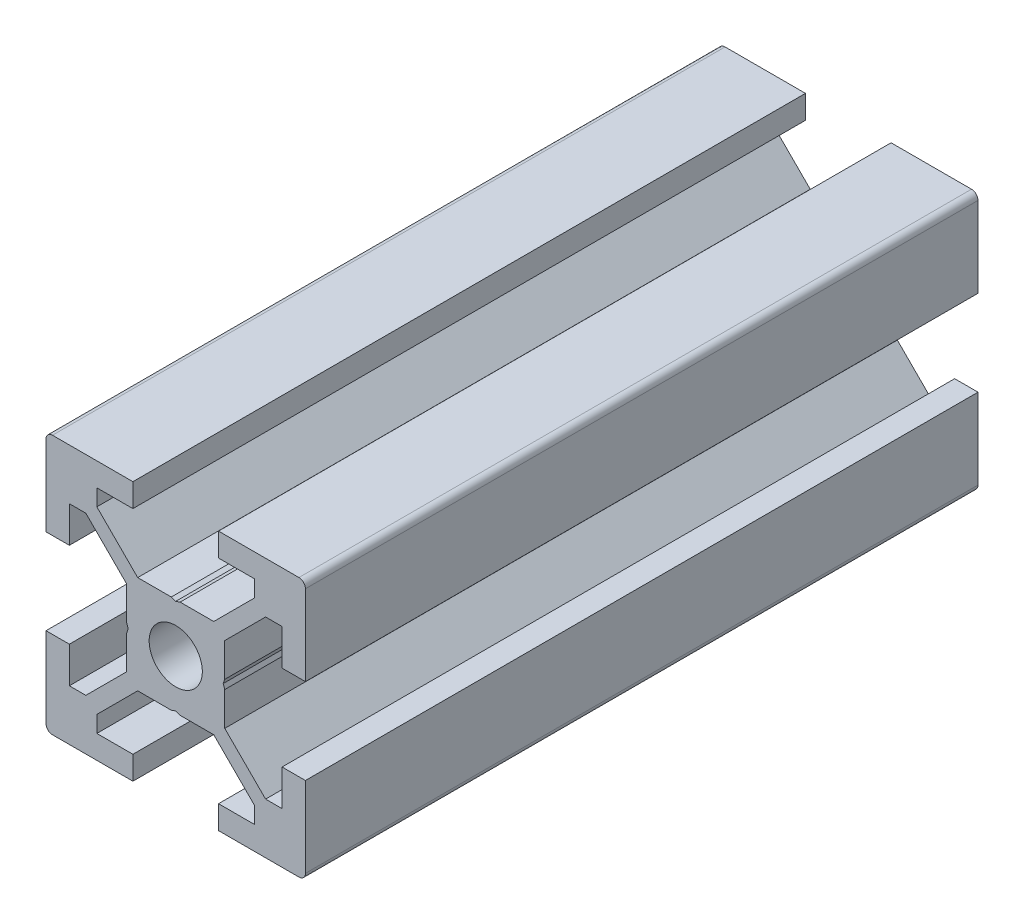
SolidWorks part; units mm, degrees
ref_plane "Front Plane" through (0, 0, 0) normal (0, 0, 1) x (1, 0, 0)
ref_plane "Top Plane" through (0, 0, 0) normal (0, 1, 0) x (1, 0, 0)
ref_plane "Right Plane" through (0, 0, 0) normal (1, 0, 0) x (0, 0, -1)
sketch "Sketch1" plane through (0, 0, 0) normal (0, 0, 1) x (1, 0, 0)
  line L0 (-3.3, 10) -> (-3.3, 8.2)
  line L1 (0, 0) -> (50000, 0) construction
  line L2 (-10, 3.3) -> (-10, 10)
  line L3 (-10, 10) -> (-3.3, 10)
  line L4 (0, 0) -> (0, 50000) construction
  line L5 (-10, -10) -> (10, 10) construction
  line L6 (-10, 10) -> (10, -10) construction
  line L7 (-2.9315, -3.78) -> (-0.34, -3.78)
  line L8 (-3.78, -2.9315) -> (-3.78, -0.34)
  line L9 (-2.9315, 3.78) -> (-0.34, 3.78)
  line L10 (3.78, -2.9315) -> (3.78, -0.34)
  line L11 (-3.78, -3.78) -> (3.78, 3.78) construction
  line L12 (-3.78, 3.78) -> (3.78, -3.78) construction
  line L13 (-6.08, 8.2) -> (-3.3, 8.2)
  line L14 (-8.2, 6.08) -> (-8.2, 3.3)
  line L15 (-8.2, 3.3) -> (-10, 3.3)
  line L16 (-8.2, 6.08) -> (-6.9285, 6.08)
  line L17 (-6.08, 8.2) -> (-6.08, 6.9285)
  line L18 (-6.9285, 6.08) -> (-3.78, 2.9315)
  line L19 (-6.08, 6.9285) -> (-2.9315, 3.78)
  line L20 (8.2, 6.08) -> (6.9285, 6.08)
  line L21 (8.2, 6.08) -> (8.2, 3.3)
  line L22 (8.2, 3.3) -> (10, 3.3)
  line L23 (10, 3.3) -> (10, 10)
  line L24 (10, 10) -> (3.3, 10)
  line L25 (3.3, 10) -> (3.3, 8.2)
  line L26 (6.08, 8.2) -> (3.3, 8.2)
  line L27 (6.08, 8.2) -> (6.08, 6.9285)
  line L28 (6.08, 6.9285) -> (2.9315, 3.78)
  line L29 (6.9285, 6.08) -> (3.78, 2.9315)
  line L30 (6.9285, -6.08) -> (3.78, -2.9315)
  line L31 (6.08, -6.9285) -> (2.9315, -3.78)
  line L32 (6.08, -8.2) -> (6.08, -6.9285)
  line L33 (6.08, -8.2) -> (3.3, -8.2)
  line L34 (3.3, -10) -> (3.3, -8.2)
  line L35 (10, -10) -> (3.3, -10)
  line L36 (10, -3.3) -> (10, -10)
  line L37 (8.2, -3.3) -> (10, -3.3)
  line L38 (8.2, -6.08) -> (8.2, -3.3)
  line L39 (8.2, -6.08) -> (6.9285, -6.08)
  line L40 (-6.08, -6.9285) -> (-2.9315, -3.78)
  line L41 (-6.9285, -6.08) -> (-3.78, -2.9315)
  line L42 (-6.08, -8.2) -> (-6.08, -6.9285)
  line L43 (-8.2, -6.08) -> (-6.9285, -6.08)
  line L44 (-8.2, -3.3) -> (-10, -3.3)
  line L45 (-8.2, -6.08) -> (-8.2, -3.3)
  line L46 (-6.08, -8.2) -> (-3.3, -8.2)
  line L47 (-10, -10) -> (-3.3, -10)
  line L48 (-10, -3.3) -> (-10, -10)
  line L49 (-3.3, -10) -> (-3.3, -8.2)
  line L50 (-0.34, 3.78) -> (0, 3.66)
  line L51 (0.34, 3.78) -> (0, 3.66)
  line L52 (0.34, 3.78) -> (2.9315, 3.78)
  line L53 (-3.78, -0.34) -> (-3.66, 0)
  line L54 (-3.78, 0.34) -> (-3.66, 0)
  line L55 (3.78, 0.34) -> (3.66, 0)
  line L56 (3.78, -0.34) -> (3.66, 0)
  line L57 (-0.34, -3.78) -> (0, -3.66)
  line L58 (0.34, -3.78) -> (0, -3.66)
  line L59 (3.78, 0.34) -> (3.78, 2.9315)
  line L60 (0.34, -3.78) -> (2.9315, -3.78)
  line L61 (-3.78, 0.34) -> (-3.78, 2.9315)
  circle A0 centre (0, 0) radius 2.05
  point P0 (0, 0)
  dimension "D3" = 4.1
  dimension "D1" = 20
  dimension "D2" = 20
  dimension "D4" = 7.56
  dimension "D5" = 6.7
  dimension "D6" = 6.7
  dimension "D7" = 0.6
  dimension "D8" = 3.92
  dimension "D9" = 0.34
  dimension "D10" = 0.12
extrude "Boss-Extrude1" add sketch "Sketch1" along normal blind 51.85
fillet "Fillet1" radius 0.5 4 edges at (-10, 10, 25.925) (-10, -10, 25.925) (10, -10, 25.925) (10, 10, 25.925)
